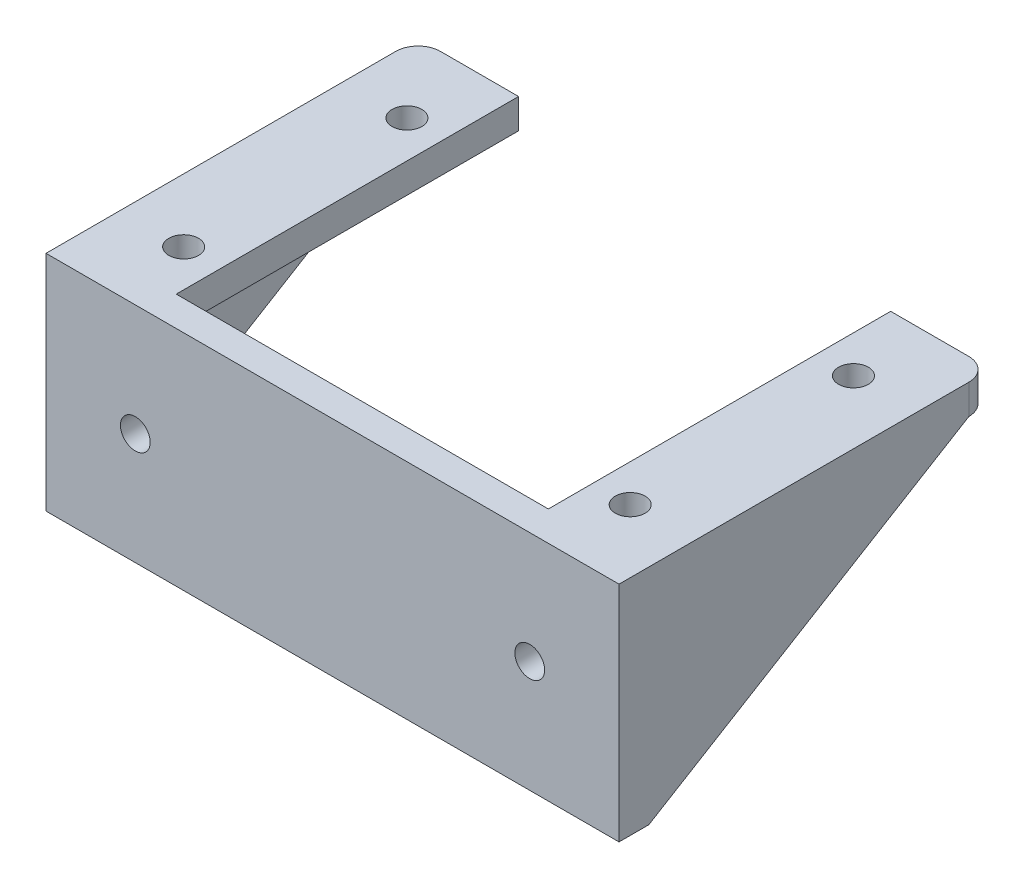
SolidWorks part; units mm, degrees
ref_plane "Płaszczyzna przednia" through (0, 0, 0) normal (0, 0, 1) x (1, 0, 0)
ref_plane "Płaszczyzna górna" through (0, 0, 0) normal (0, 1, 0) x (1, 0, 0)
ref_plane "Płaszczyzna prawa" through (0, 0, 0) normal (1, 0, 0) x (0, 0, -1)
sketch "Szkic2" plane through (0, 0, 0) normal (0, 1, 0) x (1, 0, 0)
  line L1 (-38.5, -25) -> (38.5, -25)
  line L2 (-38.5, -25) -> (-38.5, 25)
  line L3 (-38.5, 25) -> (38.5, 25)
  line L4 (38.5, -25) -> (38.5, 25)
  line L5 (-38.5, -25) -> (38.5, 25) construction
  line L6 (-38.5, 25) -> (38.5, -25) construction
  point P0 (0, 0)
  dimension "D1" = 77
  dimension "D2" = 50
extrude "Dodanie-wyciągnięcie2" add sketch "Szkic2" along normal blind 4
sketch "Szkic4" plane through (0, 0, 0) normal (0, -1, 0) x (1, 0, 0)
  line L0 (38.5, -25) -> (-38.5, -25) construction
  line L1 (25, -25) -> (-25, -25)
  line L2 (25, -25) -> (25, 21)
  line L3 (25, 21) -> (-25, 21)
  line L4 (-25, -25) -> (-25, 21)
  point P6 (0, 0)
  point P7 (0, 0)
  point P8 (0, 0)
extrude "Wytnij-wyciągnięcie1" cut sketch "Szkic4" against normal blind 4
sketch "Szkic5" plane through (0, 0, 0) normal (0, -1, 0) x (1, 0, 0)
  line L0 (-38.5, -25) -> (-38.5, 25) construction
  line L1 (38.5, 25) -> (-38.5, 25)
  line L2 (38.5, 25) -> (38.5, 21)
  line L3 (38.5, 21) -> (-38.5, 21)
  line L4 (-38.5, 25) -> (-38.5, 21)
  point P7 (0, 0)
  point P8 (0, 0)
  point P9 (0, 0)
  point P10 (0, 0)
extrude "Dodanie-wyciągnięcie3" add sketch "Szkic5" along normal blind 26
sketch "Szkic6" plane through (0, 0, 25) normal (0, 0, 1) x (1, 0, 0)
  line L0 (38.5, 4) -> (38.5, -26) construction
  line L1 (-38.5, 4) -> (-38.5, -26) construction
  line L2 (38.5, -26) -> (-38.5, -26) construction
  circle A0 centre (26.5, -11) radius 2
  circle A1 centre (-26.5, -11) radius 2
  dimension "D1" = 12
  dimension "D2" = 12
  dimension "D3" = 15
  dimension "D4" = 15
extrude "Wytnij-wyciągnięcie2" cut sketch "Szkic6" against normal up to next
fillet "Zaokrąglenie1" radius 3 2 edges at (-38.5, 2, -25) (38.5, 2, -25)
sketch "Szkic7" plane through (-38.5, 0, 0) normal (-1, 0, 0) x (0, 0, 1)
  line L0 (21, -26) -> (21, 0)
  line L1 (21, 0) -> (-22, 0)
  line L2 (-22, 0) -> (21, -26)
extrude "Dodanie-wyciągnięcie4" add sketch "Szkic7" against normal blind 4
sketch "Szkic8" plane through (38.5, 0, 0) normal (1, 0, 0) x (0, 0, -1)
  line L0 (-21, -26) -> (22, 0)
  line L1 (22, 0) -> (-21, 0)
  line L2 (-21, 0) -> (-21, -26)
extrude "Dodanie-wyciągnięcie5" add sketch "Szkic8" against normal blind 4
sketch "Szkic9" plane through (0, 4, 0) normal (0, 1, 0) x (1, 0, 0)
  line L0 (-38.5, 22) -> (-38.5, -25) construction
  line L1 (38.5, -25) -> (38.5, 22) construction
  line L2 (35.5, 25) -> (25, 25) construction
  line L3 (-25, 25) -> (-35.5, 25) construction
  circle A0 centre (-30, 15) radius 2
  circle A1 centre (-30, -15) radius 2
  circle A2 centre (30, 15) radius 2
  circle A3 centre (30, -15) radius 2
  dimension "D1" = 8.5
  dimension "D2" = 8.5
  dimension "D3" = 8.5
  dimension "D4" = 8.5
  dimension "D5" = 10
  dimension "D6" = 40
  dimension "D7" = 10
  dimension "D8" = 40
extrude "Wytnij-wyciągnięcie5" cut sketch "Szkic9" against normal up to next
